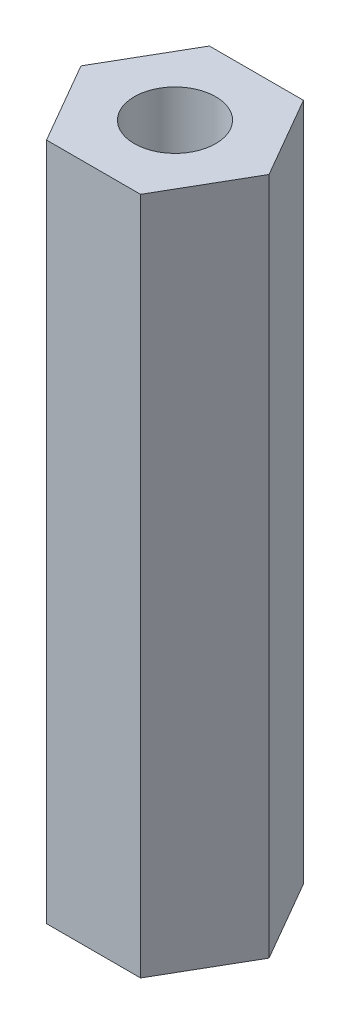
SolidWorks part; units mm, degrees
ref_plane "Front Plane" through (0, 0, 0) normal (0, 0, 1) x (1, 0, 0)
ref_plane "Top Plane" through (0, 0, 0) normal (0, 1, 0) x (1, 0, 0)
ref_plane "Right Plane" through (0, 0, 0) normal (1, 0, 0) x (0, 0, -1)
sketch "Sketch1" plane through (0, 0, 0) normal (0, 1, 0) x (1, 0, 0)
  line L1 (-3.4641, 0) -> (-1.7321, -3)
  line L2 (-1.7321, -3) -> (1.7321, -3)
  line L3 (1.7321, -3) -> (3.4641, 0)
  line L4 (3.4641, 0) -> (1.7321, 3)
  line L5 (1.7321, 3) -> (-1.7321, 3)
  line L6 (-1.7321, 3) -> (-3.4641, 0)
  circle A0 centre (0, 0) radius 3 construction
  dimension "D1" = 6
extrude "Boss-Extrude1" add sketch "Sketch1" along normal blind 25
sketch "Sketch2" plane through (0, 25, 0) normal (0, 1, 0) x (1, 0, 0)
  circle A0 centre (0, 0) radius 1.5
  dimension "D1" = 3
extrude "Cut-Extrude1" cut sketch "Sketch2" against normal blind 25
